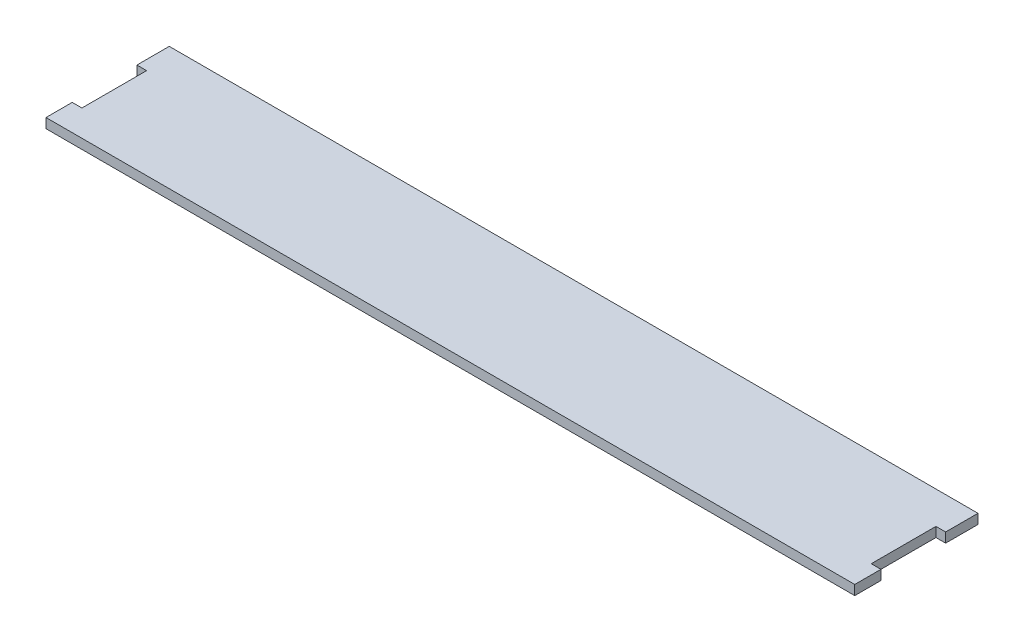
SolidWorks part; units mm, degrees
ref_plane "Front Plane" through (0, 0, 0) normal (0, 0, 1) x (1, 0, 0)
ref_plane "Top Plane" through (0, 0, 0) normal (0, 1, 0) x (1, 0, 0)
ref_plane "Right Plane" through (0, 0, 0) normal (1, 0, 0) x (0, 0, -1)
sketch "Sketch1" plane through (0, 0, 0) normal (0, 1, 0) x (1, 0, 0)
  line L1 (0, 0) -> (250, 0)
  line L2 (0, 0) -> (0, 40)
  line L3 (0, 40) -> (250, 40)
  line L4 (250, 0) -> (250, 40)
  dimension "D1" = 250
  dimension "D2" = 40
extrude "Boss-Extrude1" add sketch "Sketch1" along normal blind 3
sketch "Sketch2" plane through (0, 3, 0) normal (0, 1, 0) x (1, 0, 0)
  line L0 (0, 40) -> (0, 0) construction
  line L1 (0, 30) -> (3, 30)
  line L2 (0, 30) -> (0, 10)
  line L3 (0, 10) -> (3, 10)
  line L4 (3, 30) -> (3, 10)
  line L5 (250, 40) -> (0, 40) construction
  line L6 (250, 0) -> (250, 40) construction
  line L7 (250, 30) -> (247, 30)
  line L8 (250, 30) -> (250, 10)
  line L9 (250, 10) -> (247, 10)
  line L10 (247, 30) -> (247, 10)
  line L11 (0, 0) -> (250, 0) construction
  dimension "D1" = 3
  dimension "D2" = 20
  dimension "D3" = 10
  dimension "D4" = 3
  dimension "D5" = 10
  dimension "D6" = 20
extrude "Cut-Extrude1" cut sketch "Sketch2" against normal through all
sketch "Sketch4" plane through (0, 0, 0) normal (0, -1, 0) x (1, 0, 0)
  line L0 (0, -10) -> (0, 0) construction
  line L1 (250, 0) -> (0, 0)
  line L2 (250, 0) -> (250, -1.9)
  line L3 (250, -1.9) -> (0, -1.9)
  line L4 (0, 0) -> (0, -1.9)
  dimension "D1" = 1.9
extrude "Cut-Extrude2" cut sketch "Sketch4" against normal up to next
